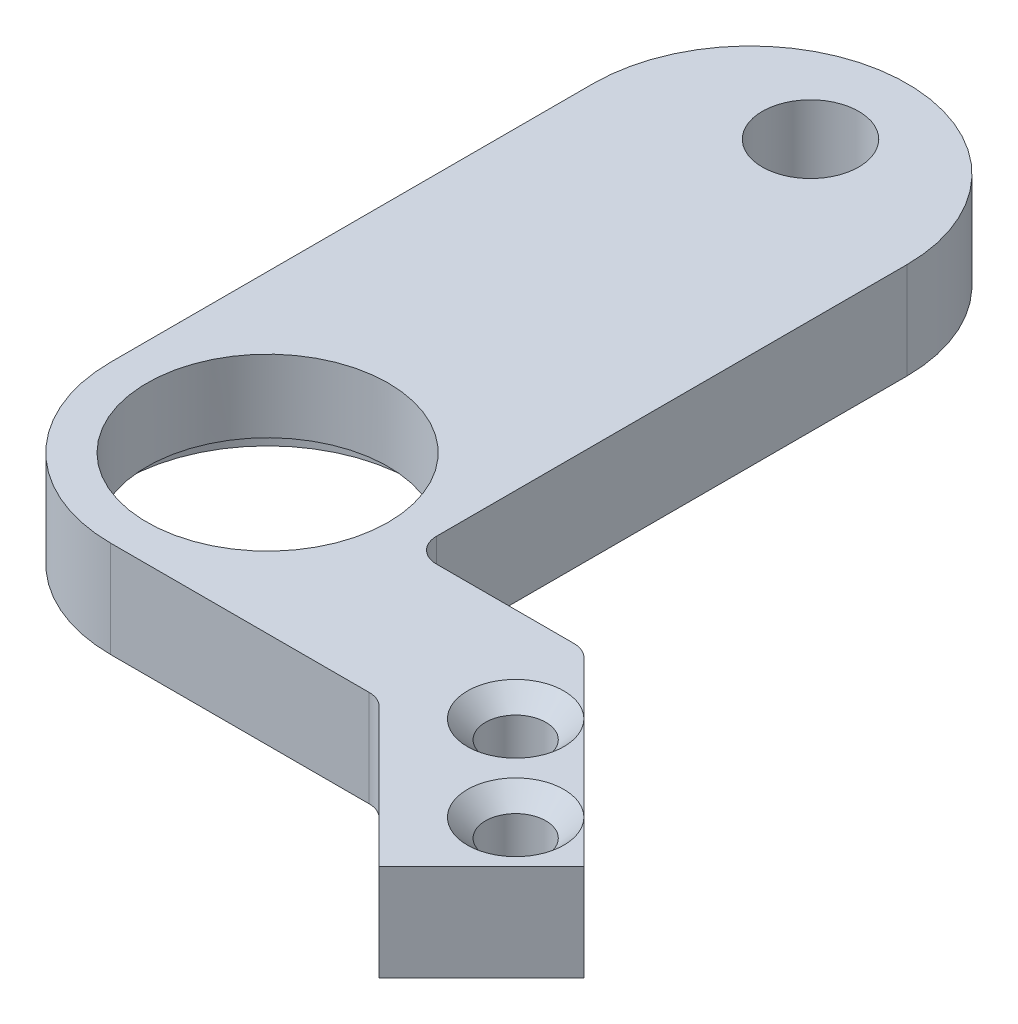
SolidWorks part; units mm, degrees
material "6061 Alloy"
ref_plane "Front Plane" through (0, 0, 0) normal (0, 0, 1) x (1, 0, 0)
ref_plane "Top Plane" through (0, 0, 0) normal (0, 1, 0) x (1, 0, 0)
ref_plane "Right Plane" through (0, 0, 0) normal (1, 0, 0) x (0, 0, -1)
ref_plane "Plane1" through (0, -2, 0) normal (0, -1, 0) x (1, 0, 0)
sketch "Sketch1" plane through (0, -2, 0) normal (0, -1, 0) x (1, 0, 0)
  line L0 (11.1243, 26.5) -> (-6.5, 26.5)
  line L1 (-6.5, 26.5) -> (-6.5, 0)
  line L2 (6.5, 0) -> (6.5, 20.5)
  line L3 (6.5, 20.5) -> (13.6096, 20.5)
  line L4 (13.6096, 20.5) -> (13.6096, 36.1006)
  line L5 (13.6096, 36.1006) -> (11.1243, 38.5859)
  line L6 (11.1243, 38.5859) -> (11.1243, 26.5)
  arc A0 (-6.5, 0) -> (6.5, 0) centre (0, 0) ccw
extrude "Boss-Extrude1" add sketch "Sketch1" against normal blind 4
draft "Draft1" type of draft neutral plane draft angle 45 faces to draft 1 face at (13.6096, 0, 28.3003) neutral plane through (6.5, 2, 20.5) neutral plane normal (0, 0, -1) parameters "D1"=45
draft "Draft2" type of draft neutral plane draft angle 45 faces to draft 1 face at (11.1243, 0, 32.5429) neutral plane through (11.1243, 2, 26.5) neutral plane normal (0, 0, 1) parameters "D1"=45
ref_plane "Plane2" through (0, 0, 20) normal (0, 0, 1) x (1, 0, 0)
sketch "Sketch2" plane through (0, 0, 20) normal (0, 0, 1) x (1, 0, 0)
  line L1 (0, 3.1955) -> (0, -2)
  line L2 (0, -2) -> (6, -2)
  line L3 (6, -2) -> (6, -1)
  line L4 (6, -1) -> (5, -1)
  line L5 (5, -1) -> (5, 3.1955)
  line L8 (0, 3.1955) -> (0, -2) construction
  line L9 (5, 3.1955) -> (0, 3.1955)
revolve "Cut-Revolve1" cut sketch "Sketch2" angle 360 about L8
hole_wizard "Ø4.0 (4) Diameter Hole1" positions "Sketch4" profile "Sketch3" hole size "Ø4.0" standard "ANSI Metric" end condition through all
sketch "Sketch4" plane through (0, 2, 0) normal (0, 1, 0) x (1, 0, 0)
  point P0 (0, 2.5)
sketch "Sketch3" plane through (0, 2, -2.5) normal (1, 0, 0) x (0, 0, 1)
  line L0 (0, 0) -> (0, 4)
  line L1 (0, 4) -> (2, 4)
  line L2 (2, 4) -> (2, 0)
  line L5 (2, 0) -> (0, 0)
  line L11 (0, -6.35) -> (0, 107.95) construction
  dimension "Thru Hole Dia." = 4
  dimension "Thru Hole Depth" = 4
fillet "Fillet1" radius 1 3 edges at (6.5, 0, 20.5) (11.1243, 0, 26.5) (13.6096, 0, 20.5)
fillet "Fillet2" radius 6.5 1 edges at (-6.5, 0, 26.5)
hole_wizard "CSK for M3 SFHCS2" positions "3DSketch1" profile "Sketch7" countersink size "M3" standard "ANSI Metric" end condition through all
sketch3d "3DSketch1"
  line L0 (13.9025, 2, 20.7929) -> (21.4099, 2, 28.3003) construction
  line L1 (21.4099, 2, 28.3003) -> (17.1673, 2, 32.5429) construction
  point P0 (18.2279, 2, 27.9467)
  point P2 (14.6924, 2, 24.4112)
  dimension "D1" = 2
  dimension "D2" = 2
  dimension "D3" = 2.5
  dimension "D4" = 5
sketch "Sketch7" plane through (18.2279, 2, 27.9467) normal (1, 0, 0) x (0, 0, 1)
  line L0 (0, 0) -> (0, 4)
  line L1 (0, 4) -> (1.25, 4)
  line L2 (1.25, 4) -> (1.25, 0.75)
  line L3 (1.25, 0.75) -> (2, 0)
  line L5 (2, 0) -> (0, 0)
  line L6 (-1.25, 0.75) -> (-2, 0) construction
  line L11 (0, -6.35) -> (0, 107.95) construction
  dimension "Thru Hole Dia." = 2.5
  dimension "Thru Hole Depth" = 4
  dimension "Near C'Sink Dia." = 4
  dimension "Near C'Sink Angle" = 90
